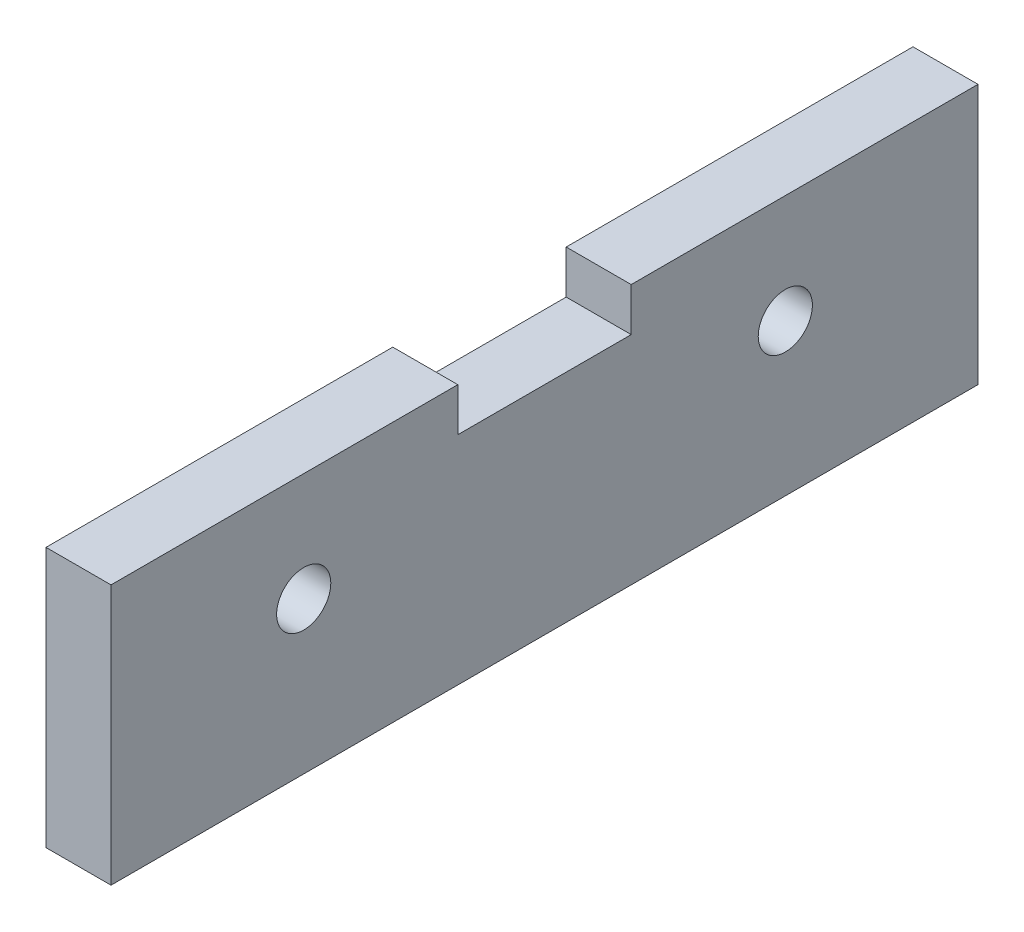
SolidWorks part; units mm, degrees
ref_plane "Front Plane" through (0, 0, 0) normal (0, 0, 1) x (1, 0, 0)
ref_plane "Top Plane" through (0, 0, 0) normal (0, 1, 0) x (1, 0, 0)
ref_plane "Right Plane" through (0, 0, 0) normal (1, 0, 0) x (0, 0, -1)
sketch "Sketch1" plane through (0, 0, 0) normal (1, 0, 0) x (0, 0, -1)
  line L1 (20, -6) -> (-20, -6)
  line L2 (20, -6) -> (20, 6)
  line L3 (20, 6) -> (-20, 6)
  line L4 (-20, -6) -> (-20, 6)
  line L5 (20, -6) -> (-20, 6) construction
  line L6 (20, 6) -> (-20, -6) construction
  point P0 (0, 0)
  dimension "D1" = 40
  dimension "D2" = 12
extrude "Boss-Extrude1" add sketch "Sketch1" along normal blind 3
sketch "Sketch2" plane through (3, 0, 0) normal (1, 0, 0) x (0, 0, -1)
  line L0 (20, 6) -> (-20, 6) construction
  line L1 (-4, 6) -> (4, 6)
  line L2 (-4, 6) -> (-4, 4)
  line L3 (-20, -6) -> (20, -6) construction
  line L4 (-4, 4) -> (4, 4)
  line L5 (4, 6) -> (4, 4)
  line L6 (-20, 6) -> (-20, -6) construction
  circle A0 centre (-11.11, 1) radius 1.25
  point P11 (0, 6)
  dimension "D3" = 2.5
  dimension "D4" = 2
  dimension "D5" = 20
  dimension "D1" = 7
  dimension "D2" = 8
extrude "Cut-Extrude1" cut sketch "Sketch2" against normal blind 5
mirror "Mirror1" about plane through (0, 0, 0) normal (0, 0, 1) of "Cut-Extrude1"
